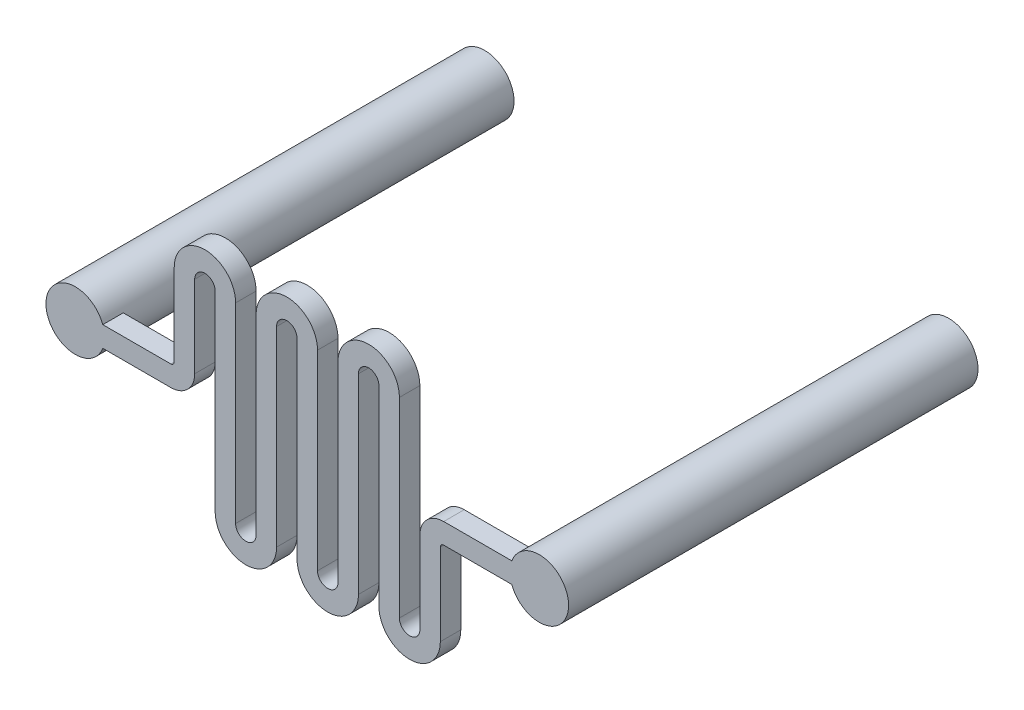
SolidWorks part; units mm, degrees
ref_plane "Front Plane" through (0, 0, 0) normal (0, 0, 1) x (1, 0, 0)
ref_plane "Top Plane" through (0, 0, 0) normal (0, 1, 0) x (1, 0, 0)
ref_plane "Right Plane" through (0, 0, 0) normal (1, 0, 0) x (0, 0, -1)
sketch "Sketch2" plane through (0, 0, 0) normal (0, 0, 1) x (1, 0, 0)
  line L3 (-20.5, -0.75) -> (-13.5, -0.75)
  line L6 (-11.75, 1) -> (-11.75, 7)
  line L9 (-10.25, 7) -> (-10.25, 0)
  line L12 (-10.25, 0) -> (-10.25, -7)
  line L15 (-5.75, -7) -> (-5.75, 0)
  line L18 (-5.75, 0) -> (-5.75, 7)
  line L21 (-4.25, 7) -> (-4.25, 0)
  line L22 (-4.25, 0) -> (-4.25, -7)
  line L23 (0.25, -7) -> (0.25, 0)
  line L24 (0.25, 0) -> (0.25, 7)
  line L25 (1.75, 7) -> (1.75, 0)
  line L26 (1.75, 0) -> (1.75, -7)
  line L27 (6.25, -7) -> (6.25, -1)
  line L28 (6.5, -0.75) -> (13.5, -0.75)
  line L29 (-20.5, 0.75) -> (-13.5, 0.75)
  line L30 (-13.25, 1) -> (-13.25, 7)
  line L31 (-8.75, 7) -> (-8.75, 0)
  line L32 (-8.75, 0) -> (-8.75, -7)
  line L33 (-7.25, -7) -> (-7.25, 0)
  line L34 (-7.25, 0) -> (-7.25, 7)
  line L35 (-2.75, 7) -> (-2.75, 0)
  line L36 (-2.75, 0) -> (-2.75, -7)
  line L37 (-1.25, -7) -> (-1.25, 0)
  line L38 (-1.25, 0) -> (-1.25, 7)
  line L39 (3.25, 7) -> (3.25, 0)
  line L40 (3.25, 0) -> (3.25, -7)
  line L41 (4.75, -7) -> (4.75, -1)
  line L42 (6.5, 0.75) -> (13.5, 0.75)
  arc A8 (-11.75, 1) -> (-13.5, -0.75) centre (-13.5, 1) cw
  arc A9 (-11.75, 7) -> (-10.25, 7) centre (-11, 7) cw
  arc A10 (-10.25, -7) -> (-5.75, -7) centre (-8, -7) ccw
  arc A11 (-5.75, 7) -> (-4.25, 7) centre (-5, 7) cw
  arc A12 (-4.25, -7) -> (0.25, -7) centre (-2, -7) ccw
  arc A13 (0.25, 7) -> (1.75, 7) centre (1, 7) cw
  arc A14 (1.75, -7) -> (6.25, -7) centre (4, -7) ccw
  arc A15 (6.25, -1) -> (6.5, -0.75) centre (6.5, -1) cw
  arc A16 (-13.25, 1) -> (-13.5, 0.75) centre (-13.5, 1) cw
  arc A17 (-13.25, 7) -> (-8.75, 7) centre (-11, 7) cw
  arc A18 (-8.75, -7) -> (-7.25, -7) centre (-8, -7) ccw
  arc A19 (-7.25, 7) -> (-2.75, 7) centre (-5, 7) cw
  arc A20 (-2.75, -7) -> (-1.25, -7) centre (-2, -7) ccw
  arc A21 (-1.25, 7) -> (3.25, 7) centre (1, 7) cw
  arc A22 (3.25, -7) -> (4.75, -7) centre (4, -7) ccw
  arc A23 (4.75, -1) -> (6.5, 0.75) centre (6.5, -1) cw
  arc A24 (13.5, -0.75) -> (13.5, 0.75) centre (13.5, 0) ccw
  arc A25 (-20.5, 0.75) -> (-20.5, -0.75) centre (-20.5, 0) ccw
  point P4 (0, 0)
  point P32 (5.5, 0)
  point P35 (-12.5, 0)
  dimension "D1" = 8
  dimension "D14" = 8
extrude "Boss-Extrude1" add sketch "Sketch2" along normal blind 1.5
ref_plane "Plane1" through (0, 0, 0) normal (0, 1, 0) x (1, 0, 0)
sketch "Sketch3" plane through (0, 0, 0) normal (0, 1, 0) x (1, 0, 0)
  line L1 (-20.5, 28.5) -> (-22.65, 28.5)
  line L2 (-20.5, -1.5) -> (-20.5, 28.5)
  line L6 (-22.65, 28.5) -> (-22.65, -1.5)
  line L7 (-22.65, -1.5) -> (-20.5, -1.5)
  dimension "D1" = 2.15
  dimension "D3" = 30
ref_plane "Plane2" through (0, 0, 0) normal (0, 1, 0) x (1, 0, 0)
sketch "Sketch4" plane through (0, 0, 0) normal (0, 1, 0) x (1, 0, 0)
  line L1 (13.5, 28.5) -> (15.65, 28.5)
  line L2 (13.5, -1.5) -> (13.5, 28.5)
  line L6 (15.65, 28.5) -> (15.65, -1.5)
  line L7 (15.65, -1.5) -> (13.5, -1.5)
  dimension "D1" = 2.15
  dimension "D3" = 30
revolve "Revolve1" add sketch "Sketch3" angle 360 about L2
revolve "Revolve2" add sketch "Sketch4" angle 360 about L2
sketch "Sketch5" plane through (0, 0, -28.5) normal (0, 0, -1) x (-1, 0, 0)
  circle A0 centre (20.5, 0) radius 1.5
  circle A1 centre (-13.5, 0) radius 1.5
  dimension "D1" = 3
  dimension "D2" = 3
extrude "Cut-Extrude1" cut sketch "Sketch5" against normal blind 28
